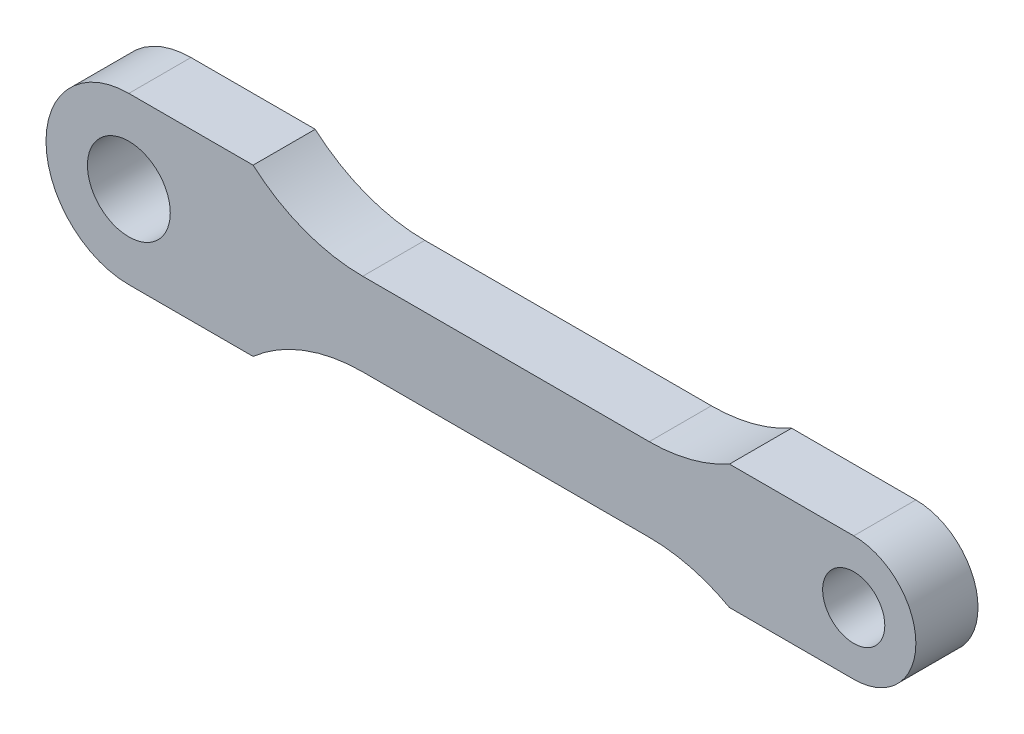
SolidWorks part; units mm, degrees
ref_plane "Front Plane" through (0, 0, 0) normal (0, 0, 1) x (1, 0, 0)
ref_plane "Top Plane" through (0, 0, 0) normal (0, 1, 0) x (1, 0, 0)
ref_plane "Right Plane" through (0, 0, 0) normal (1, 0, 0) x (0, 0, -1)
sketch "Sketch1" plane through (0, 0, 0) normal (0, 0, 1) x (1, 0, 0)
  line L0 (-17.5, 0) -> (-15.5, 0) construction
  line L1 (0, 3.5728) -> (0, -3.0291) construction
  line L2 (0, 2) -> (7.627, 2)
  line L3 (-11.5, 4) -> (-17.5, 4)
  line L4 (-17.5, -4) -> (-11.5, -4)
  line L5 (-6.2085, 2) -> (0, 2)
  line L7 (-6.2085, -2) -> (0, -2)
  line L8 (11.5, 3) -> (17.5, 3)
  line L9 (17.5, -3) -> (11.5, -3)
  line L11 (7.627, -2) -> (0, -2)
  circle A0 centre (-17.5, 0) radius 2
  arc A1 (-17.5, 4) -> (-17.5, -4) centre (-17.5, 0) ccw
  arc A2 (-11.5, 4) -> (-6.2085, 2) centre (-6.2085, 10) ccw
  arc A3 (-11.5, -4) -> (-6.2085, -2) centre (-6.2085, -10) cw
  arc A4 (17.5, 3) -> (17.5, -3) centre (17.5, 0) cw
  circle A5 centre (17.5, 0) radius 1.5
  arc A6 (11.5, 3) -> (7.627, 2) centre (7.627, 10) cw
  arc A7 (11.5, -3) -> (7.627, -2) centre (7.627, -10) ccw
  point P16 (-14.5, -4)
  dimension "D1" = 8
  dimension "D3" = 17.5
  dimension "D4" = 4
  dimension "D6" = 4
  dimension "D7" = 8
  dimension "D8" = 8
  dimension "D9" = 6
  dimension "D11" = 3
  dimension "D13" = 8
  dimension "D14" = 8
  dimension "D15" = 6
  dimension "D2" = 6
  dimension "D5" = 6
  dimension "D10" = 6
  dimension "D12" = 17.5
extrude "Boss-Extrude2" add sketch "Sketch1" along normal mid plane 3
